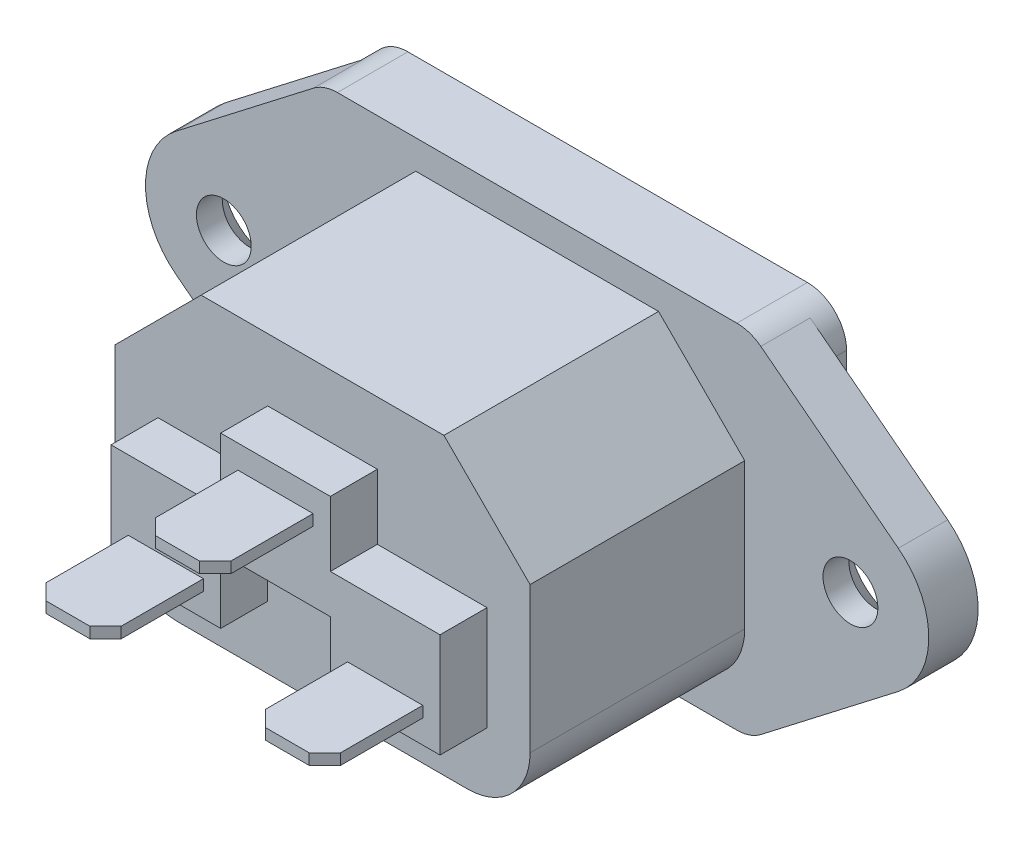
SolidWorks part; units mm, degrees
material "PA Type 6"
ref_plane "Front Plane" through (0, 0, 0) normal (0, 0, 1) x (1, 0, 0)
ref_plane "Top Plane" through (0, 0, 0) normal (0, 1, 0) x (1, 0, 0)
ref_plane "Right Plane" through (0, 0, 0) normal (1, 0, 0) x (0, 0, -1)
sketch "Sketch1" plane through (0, 0, 0) normal (0, 0, 1) x (1, 0, 0)
  line L0 (55, 0) -> (-55, 0) construction
  line L1 (0, -55) -> (0, 55) construction
  line L2 (-12.75, 11.25) -> (12.75, 11.25)
  line L3 (-12.75, -11.25) -> (12.75, -11.25)
  line L5 (-14.277, 10.7295) -> (-23.0539, 3.959)
  line L7 (-23.0539, -3.959) -> (-14.277, -10.7295)
  line L8 (23.0539, -3.959) -> (14.277, -10.7295)
  line L9 (14.277, 10.7295) -> (23.0539, 3.959)
  circle A0 centre (-20, 0) radius 1.75
  circle A1 centre (20, 0) radius 1.75
  arc A2 (-23.0539, 3.959) -> (-23.0539, -3.959) centre (-20, 0) ccw
  arc A3 (23.0539, -3.959) -> (23.0539, 3.959) centre (20, 0) ccw
  arc A4 (-12.75, 11.25) -> (-14.277, 10.7295) centre (-12.75, 8.75) ccw
  arc A5 (12.75, 11.25) -> (14.277, 10.7295) centre (12.75, 8.75) cw
  arc A6 (14.277, -10.7295) -> (12.75, -11.25) centre (12.75, -8.75) cw
  arc A7 (-14.277, -10.7295) -> (-12.75, -11.25) centre (-12.75, -8.75) ccw
  dimension "D3" = 3.5
  dimension "D8" = 2.5
  dimension "D9" = 10
  dimension "D1" = 40
  dimension "D2" = 20
  dimension "D4" = 22.5
  dimension "D5" = 11.25
  dimension "D6" = 25.5
  dimension "D7" = 12.75
extrude "Extrude1" add sketch "Sketch1" along normal blind 3.15
chamfer "Chamfer1" distance 1.5 angle 45 2 edges at (21.75, 0, 0) (-18.25, 0, 0)
sketch "Sketch2" plane through (0, 0, 0) normal (0, 0, -1) x (-1, 0, 0)
  line L0 (-12.75, 11.25) -> (12.75, 11.25)
  line L1 (-12.75, 11.25) -> (12.75, 11.25) construction
  line L2 (-15.25, 8.75) -> (-15.25, -8.75)
  line L3 (-12.75, -11.25) -> (12.75, -11.25)
  line L4 (12.75, -11.25) -> (-12.75, -11.25) construction
  line L5 (15.25, -8.75) -> (15.25, 8.75)
  arc A0 (-12.75, 11.25) -> (-15.25, 8.75) centre (-12.75, 8.75) ccw
  arc A1 (-12.75, 11.25) -> (-14.277, 10.7295) centre (-12.75, 8.75) ccw construction
  arc A2 (-15.25, -8.75) -> (-12.75, -11.25) centre (-12.75, -8.75) ccw
  arc A3 (12.75, -11.25) -> (14.277, -10.7295) centre (12.75, -8.75) ccw construction
  arc A4 (12.75, -11.25) -> (15.25, -8.75) centre (12.75, -8.75) ccw
  arc A5 (15.25, 8.75) -> (12.75, 11.25) centre (12.75, 8.75) ccw
  arc A6 (14.277, 10.7295) -> (12.75, 11.25) centre (12.75, 8.75) ccw construction
  arc A7 (-14.277, -10.7295) -> (-12.75, -11.25) centre (-12.75, -8.75) ccw construction
extrude "Extrude2" add sketch "Sketch2" along normal blind 1.35
sketch "Sketch3" plane through (0, 0, 3.15) normal (0, 0, 1) x (1, 0, 0)
  line L0 (-7.75, 9.4) -> (7.75, 9.4)
  line L1 (7.75, 9.4) -> (13.25, 3.9)
  line L2 (13.25, 3.9) -> (13.25, -5.4)
  line L3 (9.25, -9.4) -> (-9.25, -9.4)
  line L4 (-13.25, -5.4) -> (-13.25, 3.9)
  line L5 (-13.25, 3.9) -> (-7.75, 9.4)
  line L6 (2.475, 0) -> (-2.475, 0) construction
  line L7 (0, -2.475) -> (0, 2.475) construction
  arc A0 (13.25, -5.4) -> (9.25, -9.4) centre (9.25, -5.4) cw
  arc A1 (-13.25, -5.4) -> (-9.25, -9.4) centre (-9.25, -5.4) ccw
  dimension "D1" = 4
  dimension "D2" = 26.5
  dimension "D3" = 18.8
  dimension "D4" = 9.4
  dimension "D5" = 13.25
  dimension "D6" = 5.5
extrude "Extrude3" add sketch "Sketch3" along normal blind 13.7
sketch "Sketch4" plane through (0, 0, 16.85) normal (0, 0, 1) x (1, 0, 0)
  line L0 (-10.5, 1.25) -> (-3.5, 1.25)
  line L1 (-3.5, 1.25) -> (-3.5, 5.4)
  line L2 (-3.5, 5.4) -> (3.5, 5.4)
  line L3 (3.5, 5.4) -> (3.5, 1.25)
  line L4 (3.5, 1.25) -> (10.5, 1.25)
  line L5 (10.5, 1.25) -> (10.5, -5.4)
  line L6 (10.5, -5.4) -> (3.5, -5.4)
  line L7 (3.5, -5.4) -> (3.5, -1.25)
  line L8 (3.5, -1.25) -> (-3.5, -1.25)
  line L9 (-3.5, -1.25) -> (-3.5, -5.4)
  line L10 (-3.5, -5.4) -> (-10.5, -5.4)
  line L11 (-10.5, -5.4) -> (-10.5, 1.25)
  line L13 (10.01, 0) -> (-10.01, 0) construction
  line L16 (0, -10.01) -> (0, 10.01) construction
  dimension "D1" = 1.25
  dimension "D2" = 5.4
  dimension "D3" = 5.4
  dimension "D4" = 21
  dimension "D5" = 7
  dimension "D6" = 7
  dimension "D7" = 3.5
  dimension "D8" = 7
  dimension "D9" = 3.5
  dimension "D10" = 1.25
extrude "Extrude4" add sketch "Sketch4" along normal blind 3
sketch "Sketch5" plane through (0, 0, 19.85) normal (0, 0, 1) x (1, 0, 0)
  line L0 (0, -11.66) -> (0, 11.66) construction
  line L1 (-2.4, 3.9) -> (2.4, 3.9)
  line L2 (-2.4, 3.9) -> (-2.4, 3.2)
  line L3 (-2.4, 3.2) -> (2.4, 3.2)
  line L4 (2.4, 3.9) -> (2.4, 3.2)
  line L5 (4.6, -3.2) -> (9.4, -3.2)
  line L6 (4.6, -3.2) -> (4.6, -3.9)
  line L7 (4.6, -3.9) -> (9.4, -3.9)
  line L8 (9.4, -3.2) -> (9.4, -3.9)
  line L9 (-9.4, -3.2) -> (-4.6, -3.2)
  line L10 (-9.4, -3.2) -> (-9.4, -3.9)
  line L11 (-9.4, -3.9) -> (-4.6, -3.9)
  line L12 (-4.6, -3.2) -> (-4.6, -3.9)
  line L17 (11.66, 0) -> (-11.66, 0) construction
  dimension "D1" = 4.8
  dimension "D2" = 2.4
  dimension "D3" = 9.2
  dimension "D4" = 4.6
  dimension "D5" = 3.2
  dimension "D6" = 0.7
  dimension "D7" = 3.2
extrude "Extrude5" add sketch "Sketch5" along normal blind 6.25
chamfer "Chamfer2" distance 1 angle 45 6 edges at (-9.4, -3.55, 26.1) (-4.6, -3.55, 26.1) (4.6, -3.55, 26.1) (9.4, -3.55, 26.1) (2.4, 3.55, 26.1) (-2.4, 3.55, 26.1)
sketch "Sketch6" plane through (0, 0, -1.35) normal (0, 0, -1) x (-1, 0, 0)
  line L0 (-6.7, 7.85) -> (6.7, 7.85)
  line L1 (6.7, 7.85) -> (12.2, 2.35)
  line L2 (12.2, 2.35) -> (12.2, -5.35)
  line L3 (-6.7, 7.85) -> (-12.2, 2.35)
  line L4 (-12.2, 2.35) -> (-12.2, -5.35)
  line L5 (-9.7, -7.85) -> (9.7, -7.85)
  line L6 (15.0975, 0) -> (-15.0975, 0) construction
  line L7 (0, 12.375) -> (0, -12.375) construction
  arc A0 (9.7, -7.85) -> (12.2, -5.35) centre (9.7, -5.35) ccw
  arc A1 (-12.2, -5.35) -> (-9.7, -7.85) centre (-9.7, -5.35) ccw
  dimension "D1" = 2.5
  dimension "D2" = 15.7
  dimension "D3" = 7.85
  dimension "D4" = 24.4
  dimension "D5" = 12.2
  dimension "D6" = 5.5
extrude "Extrude6" cut sketch "Sketch6" against normal blind 17
fillet "Fillet1" radius 0.5 8 edges at (-12.2, -1.5, -1.35) (-11.4678, -7.1178, -1.35) (0, -7.85, -1.35) (11.4678, -7.1178, -1.35) (-9.45, 5.1, -1.35) (0, 7.85, -1.35) (12.2, -1.5, -1.35) (9.45, 5.1, -1.35)
sketch "Sketch7" plane through (0, 0, 15.65) normal (0, 0, -1) x (-1, 0, 0)
  line L0 (15.0975, 0) -> (-15.0975, 0) construction
  line L1 (-8, 0) -> (-6, 0)
  line L2 (-8, 0) -> (-8, -4)
  line L3 (-8, -4) -> (-6, -4)
  line L4 (-6, 0) -> (-6, -4)
  line L7 (6, 0) -> (8, 0)
  line L8 (6, 0) -> (6, -4)
  line L9 (6, -4) -> (8, -4)
  line L10 (8, 0) -> (8, -4)
  line L11 (0, 12.375) -> (0, -12.375) construction
  dimension "D1" = 2
  dimension "D2" = 12
  dimension "D3" = 4
  dimension "D4" = 4
  dimension "D5" = 6
extrude "Extrude7" add sketch "Sketch7" along normal blind 14
sketch "Sketch8" plane through (0, 0, 15.65) normal (0, 0, -1) x (-1, 0, 0)
  line L0 (15.0975, 0) -> (-15.0975, 0) construction
  line L1 (-1, 4) -> (1, 4)
  line L2 (-1, 4) -> (-1, 0)
  line L3 (-1, 0) -> (1, 0)
  line L4 (1, 4) -> (1, 0)
  line L5 (0, 12.375) -> (0, -12.375) construction
  dimension "D1" = 4
  dimension "D2" = 2
  dimension "D3" = 1
extrude "Extrude8" add sketch "Sketch8" along normal blind 16.5
chamfer "Chamfer3" distance 0.75 angle 45 12 edges at (1, 2, -0.85) (0, 0, -0.85) (-1, 2, -0.85) (0, 4, -0.85) (-6, -2, 1.65) (-7, -4, 1.65) (-8, -2, 1.65) (-7, 0, 1.65) (7, 0, 1.65) (8, -2, 1.65) (7, -4, 1.65) (6, -2, 1.65)
